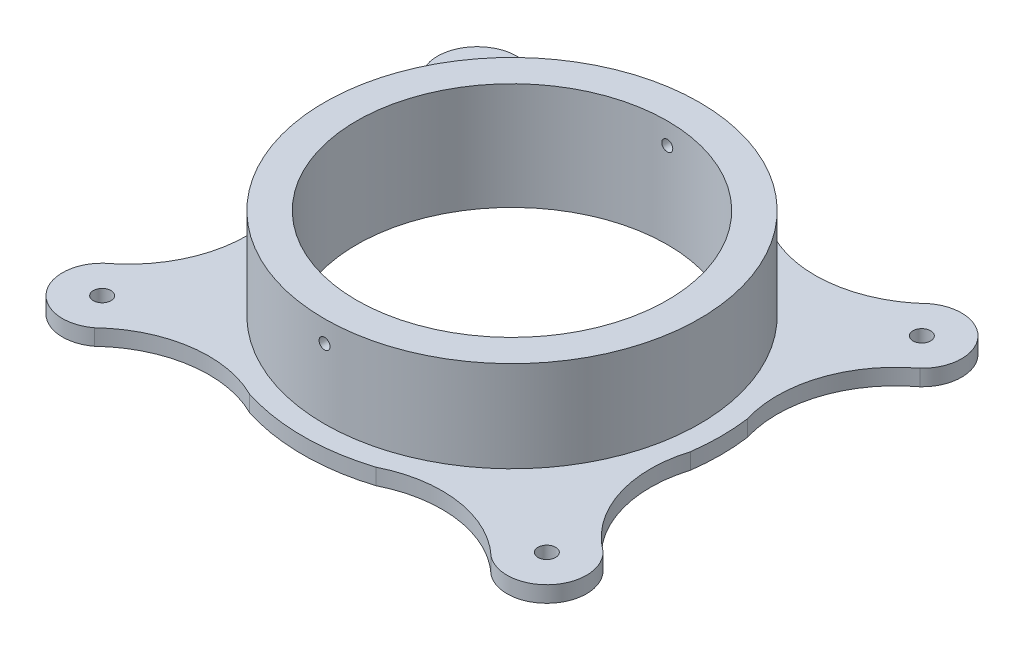
SolidWorks part; units mm, degrees
ref_plane "前视基准面" through (0, 0, 0) normal (0, 0, 1) x (1, 0, 0)
ref_plane "上视基准面" through (0, 0, 0) normal (0, 1, 0) x (1, 0, 0)
ref_plane "右视基准面" through (0, 0, 0) normal (1, 0, 0) x (0, 0, -1)
sketch "草图1" plane through (0, 0, 0) normal (0, 1, 0) x (1, 0, 0)
  line L0 (-64.683, 0) -> (63.4787, 0) construction
  line L1 (0, 51.7) -> (0, -47.2719) construction
  line L3 (41.5, -35) -> (-41.5, -35) construction
  line L4 (41.5, -35) -> (41.5, 35) construction
  line L5 (41.5, 35) -> (-41.5, 35) construction
  line L6 (-41.5, -35) -> (-41.5, 35) construction
  line L7 (41.5, -35) -> (-41.5, 35) construction
  line L8 (41.5, 35) -> (-41.5, -35) construction
  circle A0 centre (0, 0) radius 27.5 construction
  arc A2 (37.0224, 40.9121) -> (46.5719, 29.5891) centre (41.5, 35) cw
  arc A3 (-37.0224, -40.9121) -> (-46.5719, -29.5891) centre (-41.5, -35) cw
  arc A4 (37.0224, -40.9121) -> (46.5719, -29.5891) centre (41.5, -35) ccw
  arc A5 (-38.6311, 5.3518) -> (-38.6311, -5.3518) centre (0, 0) ccw
  arc A8 (-37.0224, 40.9121) -> (-46.5719, 29.5891) centre (-41.5, 35) ccw
  arc A15 (-11.7928, -37.1743) -> (11.7928, -37.1743) centre (0, 0) ccw
  arc A16 (38.6311, -5.3518) -> (38.6311, 5.3518) centre (0, 0) ccw
  arc A17 (11.7928, 37.1743) -> (-11.7928, 37.1743) centre (0, 0) ccw
  arc A18 (-11.7928, 37.1743) -> (-37.0224, 40.9121) centre (-21.7506, 56.9775) cw
  arc A19 (-38.6311, 5.3518) -> (-46.5719, 29.5891) centre (-59.8304, 11.8258) ccw
  arc A20 (-38.6311, -5.3518) -> (-46.5719, -29.5891) centre (-59.8304, -11.8258) cw
  arc A21 (-11.7928, -37.1743) -> (-37.0224, -40.9121) centre (-21.7506, -56.9775) ccw
  arc A22 (11.7928, -37.1743) -> (37.0224, -40.9121) centre (21.7506, -56.9775) cw
  arc A23 (38.6311, -5.3518) -> (46.5719, -29.5891) centre (59.8304, -11.8258) ccw
  arc A24 (38.6311, 5.3518) -> (46.5719, 29.5891) centre (59.8304, 11.8258) cw
  arc A25 (11.7928, 37.1743) -> (37.0224, 40.9121) centre (21.7506, 56.9775) ccw
  dimension "D1" = 70
  dimension "D2" = 55
  dimension "D3" = 83
  dimension "D4" = 78
extrude "凸台-拉伸2" add sketch "草图1" along normal blind 3
ref_plane "基准面1" through (0, 3, 0) normal (0, 1, 0) x (1, 0, 0)
sketch "草图2" plane through (0, 3, 0) normal (0, 1, 0) x (1, 0, 0)
  circle A0 centre (0, 0) radius 35
  dimension "D1" = 70
extrude "凸台-拉伸3" add sketch "草图2" along normal blind 17
ref_plane "基准面2" through (0, 20, 0) normal (0, 1, 0) x (1, 0, 0)
sketch "草图3" plane through (0, 20, 0) normal (0, 1, 0) x (1, 0, 0)
  circle A0 centre (0, 0) radius 25
  dimension "D1" = 50
ref_plane "基准面3" through (0, 0, 0) normal (1, 0, 0) x (0, 0, -1)
ref_plane "基准面4" through (0, 0, 0) normal (0, 0, 1) x (1, 0, 0)
hole_wizard "M2.5 螺纹孔1" positions "草图9" profile "草图10" tap size "M2.5" standard "GB"
sketch "草图9" plane through (0, 0, 0) normal (0, 0, 1) x (1, 0, 0)
  line L1 (25, 20) -> (-25, 20) construction
  point P0 (0, 16)
  dimension "D1" = 4
sketch "草图10" plane through (0, 16, 0) normal (1, 0, 0) x (0, 1, 0)
  line L0 (0, 0) -> (0, 42.4163)
  line L1 (0, 42.4163) -> (1.025, 42.4163)
  line L2 (1.025, 42.4163) -> (1.025, 0)
  line L5 (1.025, 0) -> (0, 0)
  line L11 (0, -6.35) -> (0, 107.95) construction
  dimension "通孔螺纹孔钻头直径" = 2.05
  dimension "通孔螺纹孔钻头深度" = 42.4163
cosmetic thread "孔螺蚊线26" parameters "D2"=2.5
mirror "镜向3" about plane through (0, 0, 0) normal (0, 0, 1) of "M2.5 螺纹孔1"
ref_plane "基准面5" through (0, 0, 0) normal (0, -1, 0) x (-1, 0, 0)
sketch "草图21" plane through (0, 0, 0) normal (0, -1, 0) x (-1, 0, 0)
  line L1 (-41.5, 35) -> (41.5, 35) construction
  line L2 (-41.5, 35) -> (-41.5, -35) construction
  line L3 (-41.5, -35) -> (41.5, -35) construction
  line L4 (41.5, 35) -> (41.5, -35) construction
  circle A0 centre (-41.5, 35) radius 3
  circle A1 centre (41.5, 35) radius 3
  circle A2 centre (-41.5, -35) radius 3
  circle A3 centre (41.5, -35) radius 3
hole_wizard "M4 螺纹孔2" positions "草图24" profile "草图25" tap size "M4" standard "GB" end condition through all
sketch "草图24" plane through (0, 20, 0) normal (0, 1, 0) x (1, 0, 0)
  point P0 (-41.5, 35)
  point P3 (-41.5, -35)
  point P6 (41.5, -35)
  point P9 (41.5, 35)
sketch "草图25" plane through (-41.5, 20, -35) normal (1, 0, 0) x (0, 0, 1)
  line L0 (0, 0) -> (0, 20)
  line L1 (0, 20) -> (1.65, 20)
  line L2 (1.65, 20) -> (1.65, 0)
  line L5 (1.65, 0) -> (0, 0)
  line L11 (0, -6.35) -> (0, 107.95) construction
  dimension "通孔螺纹孔钻头直径" = 3.3
  dimension "通孔螺纹孔钻头深度" = 20
cosmetic thread "孔螺蚊线14" parameters "D2"=4
cosmetic thread "孔螺蚊线15" parameters "D2"=4
cosmetic thread "孔螺蚊线16" parameters "D2"=4
cosmetic thread "孔螺蚊线17" parameters "D2"=4
ref_plane "基准面6" through (0, 20, 0) normal (0, 1, 0) x (1, 0, 0)
hole_wizard "M64 螺纹孔1" positions "草图29" profile "草图30" tap size "M64" standard "GB" end condition through all
sketch "草图29" plane through (0, 20, 0) normal (0, 1, 0) x (1, 0, 0)
  point P0 (0, 0)
sketch "草图30" plane through (0, 20, 0) normal (1, 0, 0) x (0, 0, 1)
  line L0 (0, 0) -> (0, 20)
  line L1 (0, 20) -> (29, 20)
  line L2 (29, 20) -> (29, 0)
  line L5 (29, 0) -> (0, 0)
  line L11 (0, -6.35) -> (0, 107.95) construction
  dimension "通孔螺纹孔钻头直径" = 58
  dimension "通孔螺纹孔钻头深度" = 20
cosmetic thread "孔螺蚊线23" parameters "D2"=64
